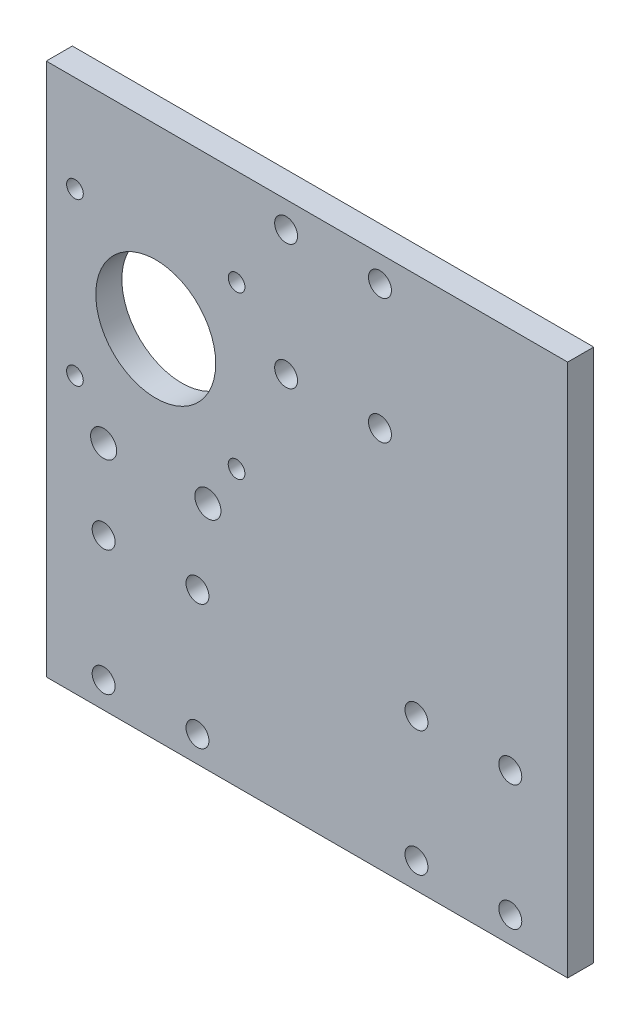
SolidWorks part; units mm, degrees
ref_plane "Front Plane" through (0, 0, 0) normal (0, 0, 1) x (1, 0, 0)
ref_plane "Top Plane" through (0, 0, 0) normal (0, 1, 0) x (1, 0, 0)
ref_plane "Right Plane" through (0, 0, 0) normal (1, 0, 0) x (0, 0, -1)
sketch "Sketch1" plane through (0, 0, 0) normal (0, 0, 1) x (1, 0, 0)
  line L1 (-50, 51.15) -> (50, 51.15)
  line L2 (-50, 51.15) -> (-50, -51.15)
  line L3 (-50, -51.15) -> (50, -51.15)
  line L4 (50, 51.15) -> (50, -51.15)
  line L5 (-50, 51.15) -> (50, -51.15) construction
  line L6 (-50, -51.15) -> (50, 51.15) construction
  point P0 (0, 0)
  dimension "D1" = 102.3
  dimension "D2" = 100
extrude "Boss-Extrude1" add sketch "Sketch1" along normal blind 5
sketch "Sketch4" plane through (0, 0, 5) normal (0, 0, 1) x (1, 0, 0)
  circle A0 centre (39, -22.15) radius 2.2
  circle A1 centre (39, -46.15) radius 2.2
  circle A2 centre (21, -46.15) radius 2.2
  circle A3 centre (21, -22.15) radius 2.2
  dimension "D7" = 4.4
  dimension "D1" = 24
  dimension "D2" = 18
extrude "Cut-Extrude1" cut sketch "Sketch4" against normal blind 5
pattern_linear "LPattern1" count 2 spacing 60 along (-1, 0, 0) of "Cut-Extrude1"
sketch "Sketch6" plane through (0, 0, 5) normal (0, 0, 1) x (1, 0, 0)
  line L0 (-29, 38.15) -> (-29, -3.85) construction
  line L5 (-50, 17.15) -> (-8, 17.15) construction
  line L6 (50, 51.15) -> (-50, 51.15) construction
  line L11 (-44.4997, 32.6497) -> (-13.5, 1.65) construction
  line L12 (-44.4997, 1.6497) -> (-13.4997, 32.651) construction
  line L13 (-50, 51.15) -> (-50, -51.15) construction
  circle A0 centre (-44.4997, 32.6497) radius 1.6
  circle A1 centre (-13.4997, 32.651) radius 1.6
  circle A2 centre (-44.4997, 1.6497) radius 1.6
  circle A3 centre (-13.5, 1.65) radius 1.6
  circle A4 centre (-29, 17.15) radius 11.5
  point P9 (-29, 17.15)
  dimension "D1" = 34
  dimension "D2" = 21
  dimension "D3" = 31
  dimension "D4" = 31
extrude "Cut-Extrude4" cut sketch "Sketch6" against normal blind 10
sketch "Sketch8" plane through (0, 0, 5) normal (0, 0, 1) x (1, 0, 0)
  line L0 (5, 34.15) -> (50, 34.15) construction
  line L5 (5, 51.15) -> (5, 17.15) construction
  line L6 (50, -51.15) -> (50, 51.15) construction
  line L11 (-4, 22.15) -> (14, 46.15) construction
  line L12 (-4, 46.15) -> (14, 22.15) construction
  circle A0 centre (-4, 46.15) radius 2.2
  circle A1 centre (14, 46.15) radius 2.2
  circle A2 centre (-4, 22.15) radius 2.2
  circle A3 centre (14, 22.15) radius 2.2
  point P8 (5, 34.15)
  dimension "D1" = 45
  dimension "D3" = 24
  dimension "D4" = 18
extrude "Cut-Extrude5" cut sketch "Sketch8" against normal blind 10
sketch "Sketch9" plane through (0, 0, 5) normal (0, 0, 1) x (1, 0, 0)
  line L0 (-29, 17.15) -> (-29, -51.15) construction
  line L1 (-50, -51.15) -> (50, -51.15) construction
  line L2 (-39, -6.85) -> (-29, -6.85) construction
  line L3 (-19, -6.85) -> (-29, -6.85) construction
  line L4 (50, 51.15) -> (-50, 51.15) construction
  circle A0 centre (-39, -6.85) radius 2.5
  circle A1 centre (-19, -6.85) radius 2.5
  dimension "D1" = 10
  dimension "D4" = 58
extrude "Cut-Extrude6" cut sketch "Sketch9" against normal blind 10
